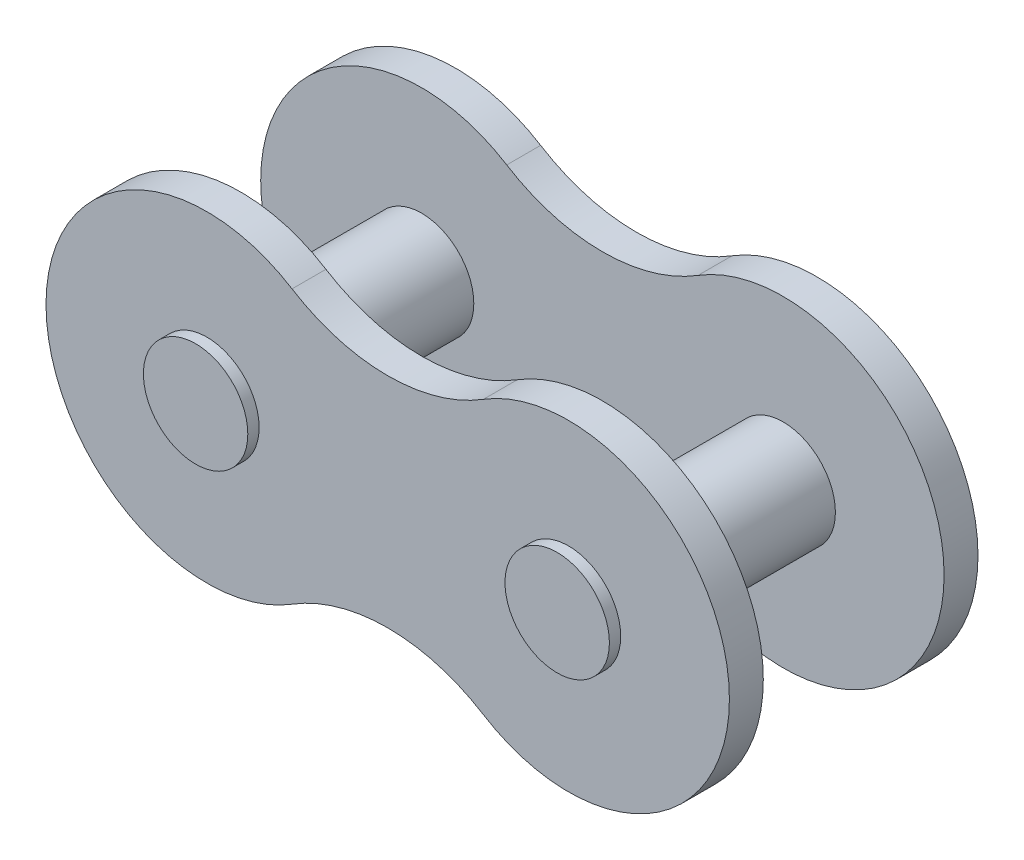
SolidWorks part; units mm, degrees
ref_plane "Front Plane" through (0, 0, 0) normal (0, 0, 1) x (1, 0, 0)
ref_plane "Top Plane" through (0, 0, 0) normal (0, 1, 0) x (1, 0, 0)
ref_plane "Right Plane" through (0, 0, 0) normal (1, 0, 0) x (0, 0, -1)
sketch "Sketch1" plane through (0, 0, 0) normal (0, 0, 1) x (1, 0, 0)
  line L0 (-4, 0) -> (4, 0) construction
  arc A0 (-2.1164, 3.0209) -> (-2.1164, -3.0209) centre (-4, 0) ccw
  arc A1 (2.1164, -3.0209) -> (2.1164, 3.0209) centre (4, 0) ccw
  arc A2 (2.1164, 3.0209) -> (-2.1164, 3.0209) centre (0, 6.4151) cw
  arc A3 (2.1164, -3.0209) -> (-2.1164, -3.0209) centre (0, -6.4151) ccw
  point P6 (0, 0)
  dimension "D1" = 7.12
  dimension "D2" = 4
extrude "Boss-Extrude1" add sketch "Sketch1" along normal blind 0.75
sketch "Sketch2" plane through (0, 0, 0.75) normal (0, 0, 1) x (1, 0, 0)
  circle A0 centre (-4, 0) radius 1.155
  circle A1 centre (4, 0) radius 1.155
  dimension "D1" = 2.31
extrude "Boss-Extrude2" add sketch "Sketch2" along normal blind 5 and the other way blind 1
ref_plane "Plane1" through (0, 0, 2.75) normal (0, 0, 1) x (1, 0, 0)
mirror "Mirror1" about plane through (0, 0, 2.75) normal (0, 0, 1) of "Boss-Extrude1"
